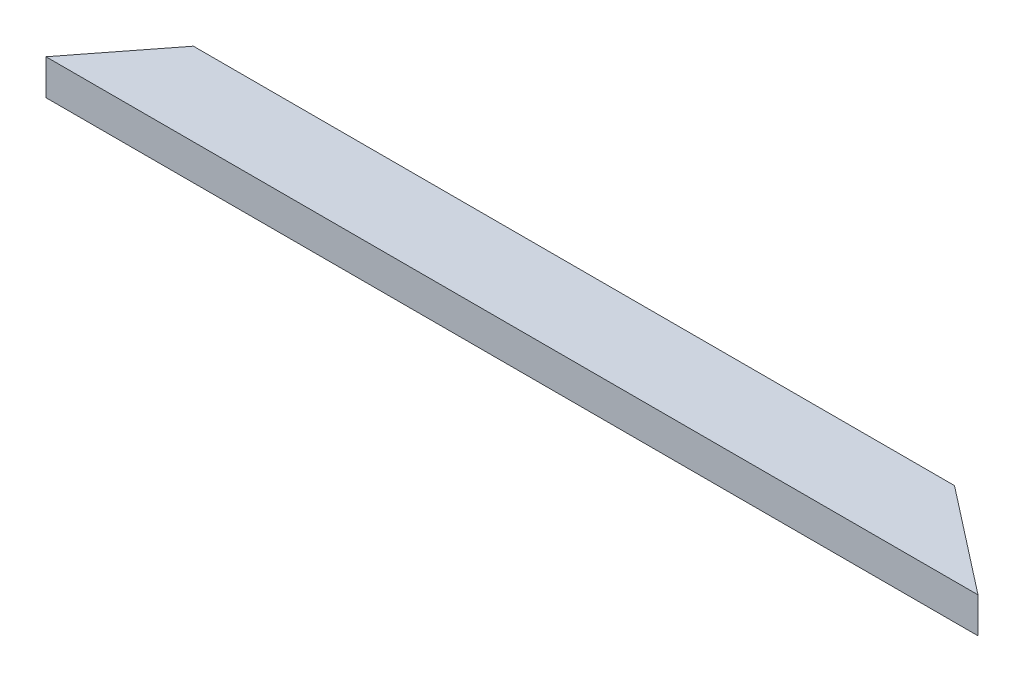
SolidWorks part; units mm, degrees
material "Pine"
ref_plane "Front Plane" through (0, 0, 0) normal (0, 0, 1) x (1, 0, 0)
ref_plane "Top Plane" through (0, 0, 0) normal (0, 1, 0) x (1, 0, 0)
ref_plane "Right Plane" through (0, 0, 0) normal (1, 0, 0) x (0, 0, -1)
sketch "Sketch1" plane through (0, 0, 0) normal (0, 1, 0) x (1, 0, 0)
  line L0 (0, 0) -> (1000, 0)
  line L1 (1000, 0) -> (885.8735, 88.9)
  line L2 (885.8735, 88.9) -> (69.2495, 88.9)
  line L3 (69.2495, 88.9) -> (0, 0)
  line L4 (500, 0) -> (500, 88.9) construction
  line L5 (0, 0) -> (377.6368, 484.7961) construction
  line L6 (377.6368, 484.7961) -> (1000, 0) construction
  dimension "D1" = 88.9
  dimension "D2" = 1000
  dimension "D3" = 816.6239
extrude "Boss-Extrude1" add sketch "Sketch1" along normal blind 38.1
